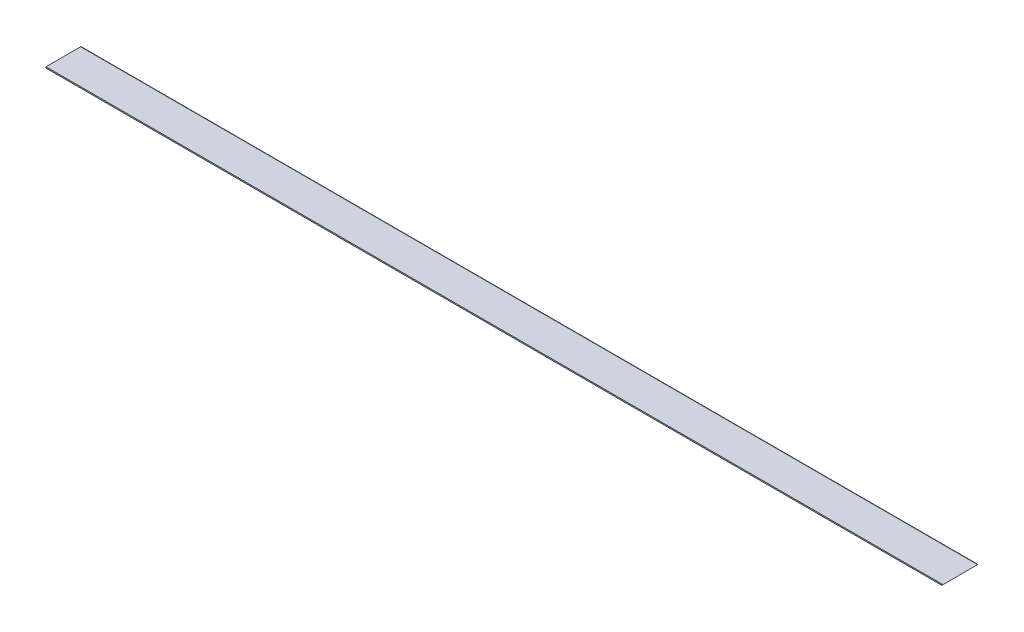
SolidWorks part; units mm, degrees
ref_plane "Front Plane" through (0, 0, 0) normal (0, 0, 1) x (1, 0, 0)
ref_plane "Top Plane" through (0, 0, 0) normal (0, 1, 0) x (1, 0, 0)
ref_plane "Right Plane" through (0, 0, 0) normal (1, 0, 0) x (0, 0, -1)
sketch "Sketch1" plane through (0, 0, 0) normal (1, 0, 0) x (0, 0, -1)
  line L0 (0, 0) -> (88, 0)
  line L1 (88, 0) -> (88, -88)
  line L2 (0, -3) -> (85, -3)
  line L3 (85, -3) -> (85, -88)
  line L4 (85, -88) -> (88, -88)
  line L5 (0, 0) -> (0, -3)
  dimension "D1" = 88
  dimension "D2" = 88
  dimension "D3" = 3
extrude "Boss-Extrude1" add sketch "Sketch1" along normal blind 2210
fillet "Fillet1" radius 3 2 edges at (1105, -3, -85) (1105, 0, -88)
sketch "Sketch2" plane through (0, 0, -88) normal (0, 0, -1) x (-1, 0, 0)
  line L0 (-2210, 0) -> (-2122, -88)
  line L1 (-2210, -88) -> (0, -88) construction
  line L2 (-2122, -88) -> (-2210, -88)
  line L3 (-2210, -88) -> (-2210, 0)
  dimension "D1" = 45
extrude "Cut-Extrude1" cut sketch "Sketch2" against normal blind 88
equation "\"D1@Boss-Extrude1\"=\"equal_angleBar_FL_3mm_length\""
equation "\"equal_angleBar_FL_3mm_length\"= 2210"
